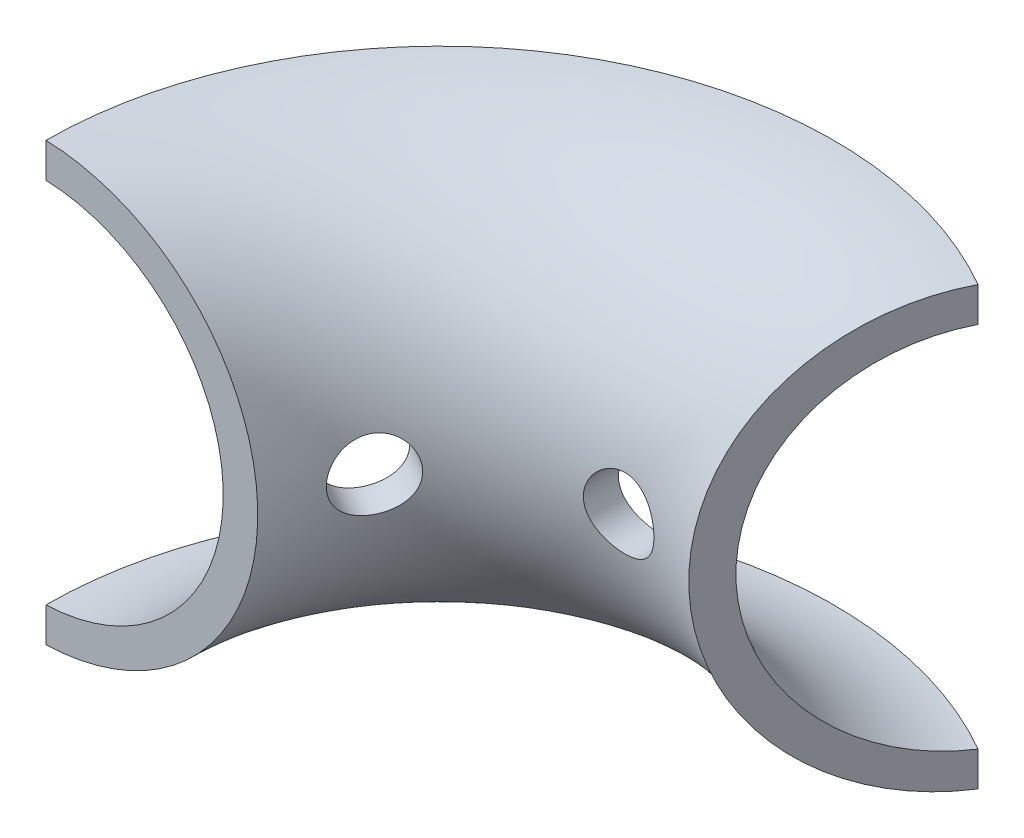
SolidWorks part; units mm, degrees
ref_plane "Front Plane" through (0, 0, 0) normal (0, 0, 1) x (1, 0, 0)
ref_plane "Top Plane" through (0, 0, 0) normal (0, 1, 0) x (1, 0, 0)
ref_plane "Right Plane" through (0, 0, 0) normal (1, 0, 0) x (0, 0, -1)
sketch "Sketch1" plane through (0, 0, 0) normal (0, 0, 1) x (1, 0, 0)
  line L2 (0.5, 16.0972) -> (0.5, 13.5508)
  line L3 (0.5, -16.0972) -> (0.5, -13.5508)
  arc A0 (0.5, -16.0972) -> (0.5, 16.0972) centre (0, 0) ccw
  arc A1 (0.5, -13.5508) -> (0.5, 13.5508) centre (0, 0) ccw
  dimension "D1" = 32.21
  dimension "D2" = 27.12
sketch "Sketch2" plane through (0, 0, 0) normal (0, 1, 0) x (1, 0, 0)
  line L0 (0, 0) -> (29.53, 0) construction
  line L1 (29.53, 0) -> (44.295, 25.5737) construction
  arc A1 (44.295, 25.5737) -> (0, 0) centre (29.53, 0) ccw
  point P3 (0, 0)
  point P4 (44.295, 25.5737)
  dimension "D1" = 29.53
  dimension "D2" = 120
sweep "Sweep1" add profiles "Sketch1" path "Sketch2"
sketch "Sketch4" plane through (0, 0, 0) normal (0, 1, 0) x (1, 0, 0)
  line L0 (29.53, 0) -> (17.9036, 6.7125)
  line L1 (17.9036, 6.7125) -> (29.53, 0)
  line L2 (29.53, 13.425) -> (29.53, 0)
  line L3 (0.5, 0) -> (16.105, 0) construction
  circle A0 centre (29.53, 0) radius 13.425
  arc A1 (36.2425, 11.6264) -> (16.105, 0) centre (29.53, 0) ccw construction
  dimension "D1" = 60
  dimension "D2" = 30
hole_wizard "Ø5.0mm Dowel Hole1" positions "3DSketch1" profile "Sketch5" hole size "Ø5.0" standard "ISO"
sketch3d "3DSketch1"
  point P0 (29.53, 0, -13.425)
  point P2 (17.9036, 0, -6.7125)
sketch "Sketch5" plane through (29.53, 0, -13.425) normal (1, 0, 0) x (0, -1, 0)
  line L0 (0, 0) -> (0, 6.5622)
  line L1 (0, 6.5622) -> (2.6, 5)
  line L2 (2.6, 5) -> (2.6, 0)
  line L5 (2.6, 0) -> (0, 0)
  line L10 (0, 6.5622) -> (-2.6, 5) construction
  line L11 (0, -6.35) -> (0, 107.95) construction
  dimension "Hole Dia." = 5.2
  dimension "Hole Depth" = 5
  dimension "Drill Angle" = 118
